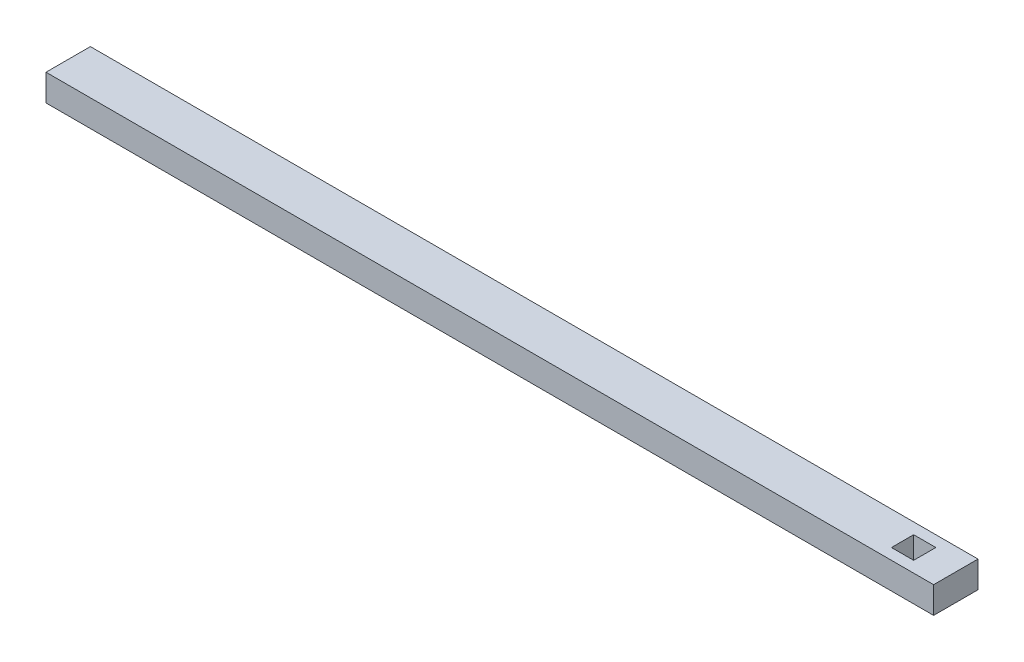
SolidWorks part; units mm, degrees
ref_plane "Front Plane" through (0, 0, 0) normal (0, 0, 1) x (1, 0, 0)
ref_plane "Top Plane" through (0, 0, 0) normal (0, 1, 0) x (1, 0, 0)
ref_plane "Right Plane" through (0, 0, 0) normal (1, 0, 0) x (0, 0, -1)
sketch "Sketch1" plane through (0, 0, 0) normal (0, 1, 0) x (1, 0, 0)
  line L1 (-100, -5) -> (100, -5)
  line L2 (-100, -5) -> (-100, 5)
  line L3 (-100, 5) -> (100, 5)
  line L4 (100, -5) -> (100, 5)
  line L5 (-100, -5) -> (100, 5) construction
  line L6 (-100, 5) -> (100, -5) construction
  point P0 (0, 0)
  dimension "D1" = 200
  dimension "D2" = 10
extrude "Boss-Extrude1" add sketch "Sketch1" along normal blind 6
sketch "Sketch2" plane through (0, 6, 0) normal (0, 1, 0) x (1, 0, 0)
  line L0 (0, 0) -> (142.3107, 0) construction
  line L1 (93, 2.5) -> (88, 2.5)
  line L2 (93, 2.5) -> (93, -2.5)
  line L3 (93, -2.5) -> (88, -2.5)
  line L4 (88, 2.5) -> (88, -2.5)
  line L6 (100, -5) -> (100, 5) construction
  dimension "D1" = 5
  dimension "D2" = 5
  dimension "D3" = 2.5
  dimension "D4" = 7
extrude "Cut-Extrude1" cut sketch "Sketch2" against normal through all
